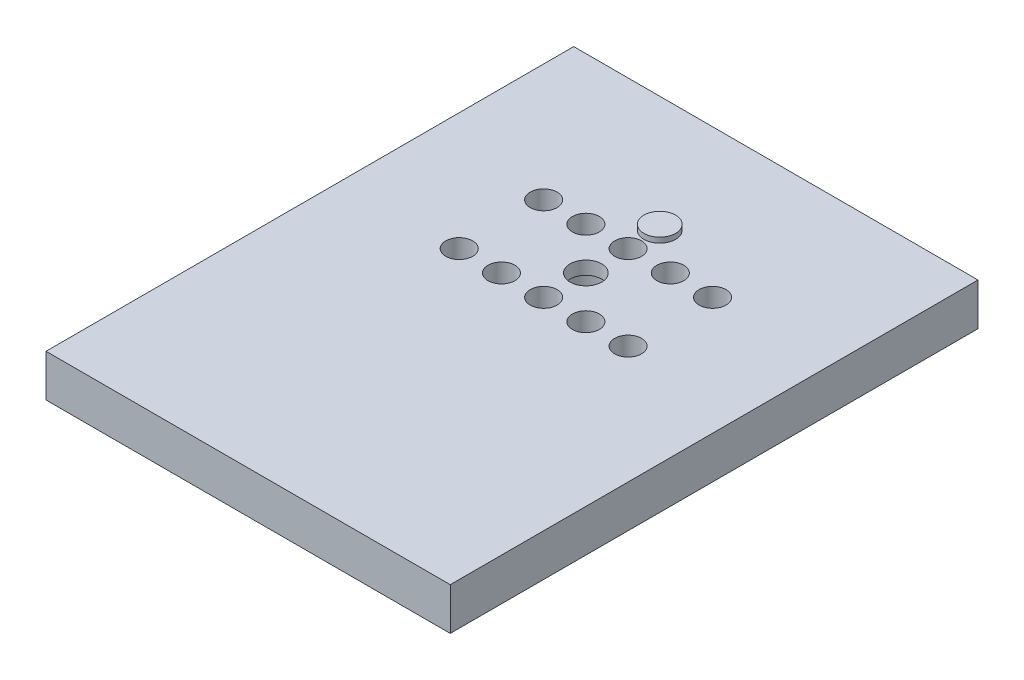
SolidWorks part; units mm, degrees
ref_plane "正面" through (0, 0, 0) normal (0, 0, 1) x (1, 0, 0)
ref_plane "平面" through (0, 0, 0) normal (0, 1, 0) x (1, 0, 0)
ref_plane "右側面" through (0, 0, 0) normal (1, 0, 0) x (0, 0, -1)
sketch "ｽｹｯﾁ1" plane through (0, 0, 0) normal (0, 1, 0) x (1, 0, 0)
  line L0 (0, 50) -> (0, 0) construction
  line L1 (-38.3, 50) -> (38.3, 50)
  line L2 (-38.3, 50) -> (-38.3, -50)
  line L3 (-38.3, -50) -> (38.3, -50)
  line L4 (38.3, 50) -> (38.3, -50)
  line L5 (-38.3, 50) -> (38.3, -50) construction
  line L6 (-38.3, -50) -> (38.3, 50) construction
  circle A0 centre (0, 14) radius 3
  point P0 (0, 0)
  dimension "D3" = 6
  dimension "D1" = 76.6
  dimension "D2" = 100
  dimension "D4" = 36
extrude "ﾎﾞｽ - 押し出し1" add sketch "ｽｹｯﾁ1" along normal blind 8
sketch "ｽｹｯﾁ2" plane through (0, 0, 0) normal (0, -1, 0) x (1, 0, 0)
  circle A0 centre (0, -14) radius 3 construction
  circle A1 centre (0, -14) radius 3 construction
  circle A2 centre (0, -14) radius 4.5
  dimension "D1" = 9
extrude "ｶｯﾄ - 押し出し1" cut sketch "ｽｹｯﾁ2" against normal blind 5.5
sketch "ｽｹｯﾁ3" plane through (0, 8, 0) normal (0, 1, 0) x (1, 0, 0)
  line L0 (0, 50) -> (0, 0) construction
  line L1 (38.3, 50) -> (-38.3, 50) construction
  circle A0 centre (0, 28) radius 3
  dimension "D1" = 6
  dimension "D2" = 22
extrude "ﾎﾞｽ - 押し出し2" add sketch "ｽｹｯﾁ3" along normal blind 1
sketch "ｽｹｯﾁ5" plane through (0, 8, 0) normal (0, 1, 0) x (1, 0, 0)
  line L0 (-38.3, 14) -> (38.3, 14) construction
  line L1 (-38.3, 50) -> (-38.3, -50) construction
  line L2 (38.3, -50) -> (38.3, 50) construction
  line L3 (0, 50) -> (0, -50) construction
  line L4 (38.3, 50) -> (-38.3, 50) construction
  line L5 (-38.3, -50) -> (38.3, -50) construction
  circle A0 centre (0, 14) radius 3 construction
  circle A1 centre (0, 22) radius 1.05
  circle A2 centre (8, 22) radius 1.05
  circle A3 centre (16, 22) radius 1.05
  circle A4 centre (-8, 22) radius 1.05
  circle A5 centre (-16, 22) radius 1.05
  circle A6 centre (-16, 6) radius 1.05
  circle A7 centre (-8, 6) radius 1.05
  circle A8 centre (16, 6) radius 1.05
  circle A9 centre (8, 6) radius 1.05
  circle A10 centre (0, 6) radius 1.05
  point P12 (0, 14)
  dimension "D1" = 2.1
  dimension "D2" = 8
  dimension "D3" = 3
  dimension "D4" = 3
extrude "ｶｯﾄ - 押し出し2" cut sketch "ｽｹｯﾁ5" against normal through all
sketch "ｽｹｯﾁ6" plane through (0, 8, 0) normal (0, 1, 0) x (1, 0, 0)
  circle A86 centre (-8, 22) radius 2.55
  circle A87 centre (-16, 22) radius 2.55
  circle A88 centre (-16, 22) radius 2.55
  circle A89 centre (0, 22) radius 2.55
  circle A90 centre (8, 22) radius 2.55
  circle A91 centre (16, 22) radius 2.55
  circle A92 centre (-8, 6) radius 2.55
  circle A93 centre (0, 6) radius 2.55
  circle A94 centre (8, 6) radius 2.55
  circle A95 centre (16, 6) radius 2.55
  circle A96 centre (-16, 6) radius 2.55
  dimension "D1" = 1.5
  dimension "D2" = 5
  dimension "D3" = 2
extrude "ｶｯﾄ - 押し出し3" cut sketch "ｽｹｯﾁ6" against normal blind 5
